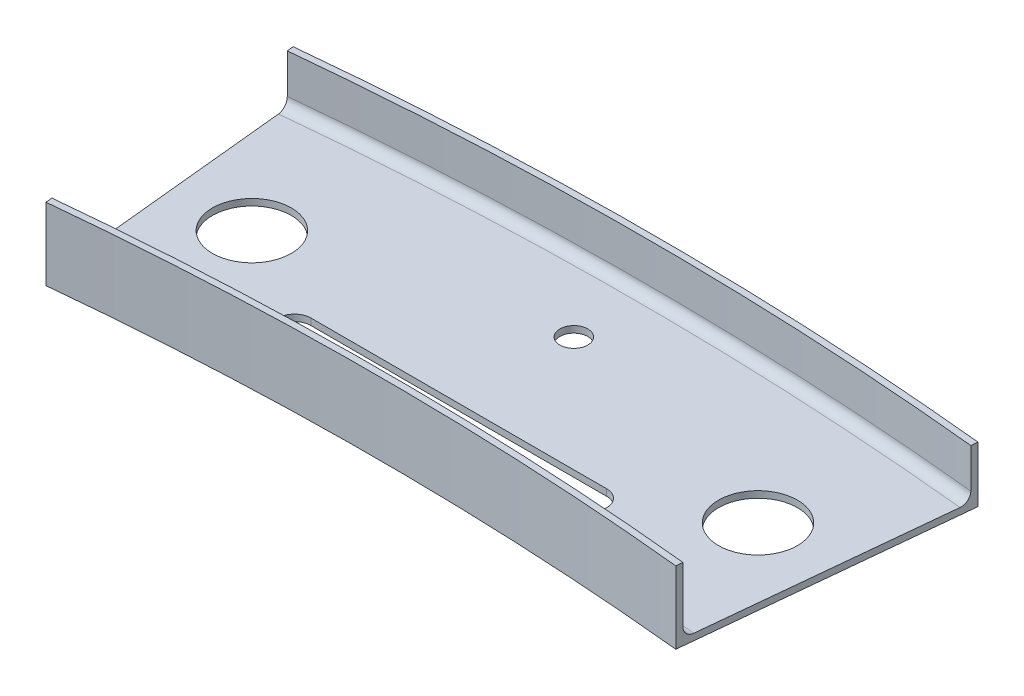
SolidWorks part; units mm, degrees
ref_plane "Front Plane" through (0, 0, 0) normal (0, 0, 1) x (1, 0, 0)
ref_plane "Top Plane" through (0, 0, 0) normal (0, 1, 0) x (1, 0, 0)
ref_plane "Right Plane" through (0, 0, 0) normal (1, 0, 0) x (0, 0, -1)
sketch "Sketch1" plane through (0, 0, 0) normal (0, 1, 0) x (1, 0, 0)
  arc A0 (-100, -5) -> (100, -5) centre (0, -1002.5) cw
  point P3 (0, 0)
  point P5 (0, 0)
  dimension "D1" = 5
  dimension "D2" = 200
sketch "Sketch2" plane through (0, 0, 0) normal (1, 0, 0) x (0, 0, -1)
  line L0 (-37, 0) -> (37, 0)
  line L1 (0, 0) -> (-5, 0) construction
  line L2 (40, 3) -> (40, 15)
  line L3 (40, 15) -> (42, 15)
  line L4 (42, 15) -> (42, -2)
  line L5 (42, -2) -> (-42, -2)
  line L6 (-42, -2) -> (-42, 20)
  line L7 (-42, 20) -> (-40, 20)
  line L8 (-40, 20) -> (-40, 3)
  arc A0 (37, 0) -> (40, 3) centre (37, 3) ccw
  arc A1 (-37, 0) -> (-40, 3) centre (-37, 3) cw
  point P11 (0, 0)
  point P14 (40, 0)
  point P17 (-40, 0)
  dimension "D6" = 3
  dimension "D1" = 15
  dimension "D2" = 20
  dimension "D3" = 80
  dimension "D4" = 2
  dimension "D5" = 2
sweep "Sweep1" add profiles "Sketch2" path "Sketch1"
sketch "Sketch3" plane through (0, 0, 0) normal (0, 1, 0) x (1, 0, 0)
  circle A0 centre (0, 18) radius 4.25
  circle A2 centre (-77, -2.9615) radius 12
  circle A3 centre (77, -2.9615) radius 12
  arc A4 (-77, -2.9615) -> (77, -2.9615) centre (0, -1002.5) cw construction
  arc A5 (95.8105, -46.7905) -> (-95.8105, -46.7905) centre (0, -1002.5) ccw construction
  arc A6 (103.99, 34.8005) -> (-103.99, 34.8005) centre (0, -1002.5) ccw construction
  point P8 (0, 40)
  point P12 (0, 0)
  dimension "D1" = 8.5
  dimension "D3" = 24
  dimension "D2" = 22
  dimension "D4" = 154
extrude "Mounting points" cut sketch "Sketch3" against normal through all both and the other way through all
sketch "Sketch4" plane through (0, 0, 0) normal (0, 1, 0) x (1, 0, 0)
  line L0 (-45, -22) -> (45, -22) construction
  line L1 (-45, -17) -> (45, -17)
  line L2 (-45, -27) -> (45, -27)
  arc A0 (-45, -17) -> (-45, -27) centre (-45, -22) ccw
  arc A1 (45, -27) -> (45, -17) centre (45, -22) ccw
  circle A3 centre (0, 18) radius 4.25 construction
  point P2 (0, -22)
  point P7 (0, 0)
  point P9 (0, 0)
  point P10 (0, 0)
  dimension "D1" = 5
  dimension "D2" = 90
  dimension "D3" = 35
extrude "Slot clearance" cut sketch "Sketch4" against normal through all both and the other way through all
